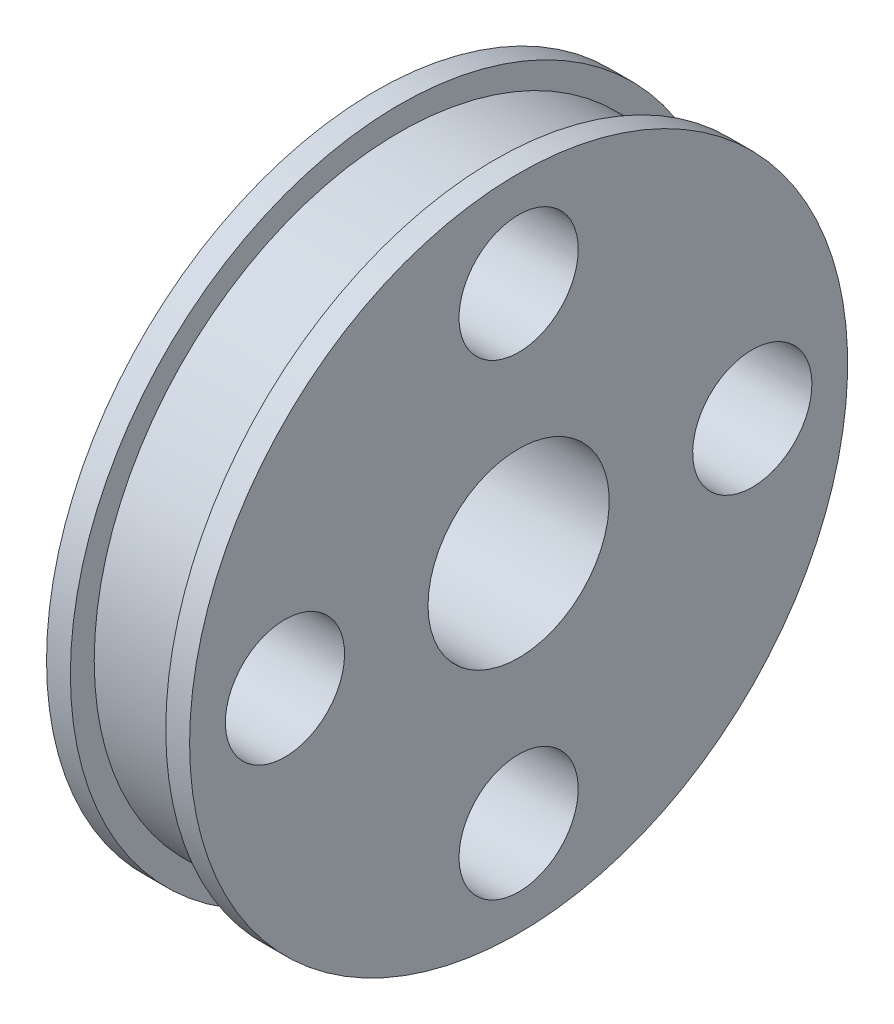
SolidWorks part; units mm, degrees
material "Cast Carbon Steel"
ref_plane "Front Plane" through (0, 0, 0) normal (0, 0, 1) x (1, 0, 0)
ref_plane "Top Plane" through (0, 0, 0) normal (0, 1, 0) x (1, 0, 0)
ref_plane "Right Plane" through (0, 0, 0) normal (1, 0, 0) x (0, 0, -1)
sketch "Sketch1" plane through (0, 0, 0) normal (0, 0, 1) x (1, 0, 0)
  line L0 (0, 0) -> (30, 0)
  line L1 (30, 0) -> (30, 50)
  line L2 (30, 50) -> (25, 50)
  line L3 (25, 50) -> (25, 45)
  line L4 (25, 45) -> (5, 45)
  line L5 (5, 45) -> (5, 50)
  line L6 (5, 50) -> (0, 50)
  line L7 (0, 50) -> (0, 0)
  line L8 (-128.929, -19) -> (132.9288, -19) construction
  point P11 (15, 45)
  dimension "D1" = 19
  dimension "D2" = 30
  dimension "D3" = 5
  dimension "D4" = 50
  dimension "D5" = 5
revolve "Revolve1" add sketch "Sketch1" angle 360 about L8
sketch "Sketch2" plane through (30, 0, 0) normal (1, 0, 0) x (0, 0, -1)
  circle A0 centre (0, 30) radius 12.5
  dimension "D2" = 25
  dimension "D1" = 30
extrude "Cut-Extrude1" cut sketch "Sketch2" against normal through all
pattern_circular "CirPattern1" count 4 over 360 about axis through (0, -19, 0) along (1, 0, 0) of "Cut-Extrude1"
